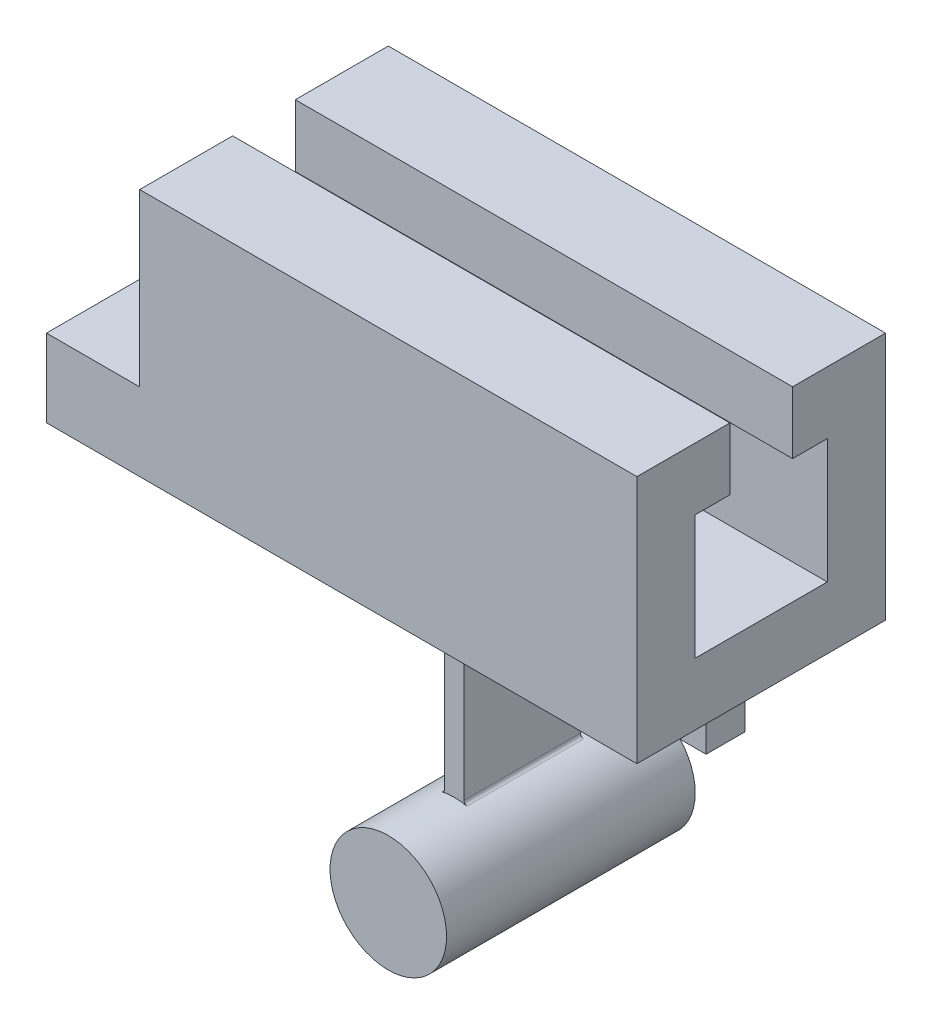
SolidWorks part; units mm, degrees
material "6061-T6 (SS)"
ref_plane "Front Plane" through (0, 0, 0) normal (0, 0, 1) x (1, 0, 0)
ref_plane "Top Plane" through (0, 0, 0) normal (0, 1, 0) x (1, 0, 0)
ref_plane "Right Plane" through (0, 0, 0) normal (1, 0, 0) x (0, 0, -1)
sketch "Sketch1" plane through (0, 0, 0) normal (1, 0, 0) x (0, 0, -1)
  line L1 (-25.4, -25.4) -> (25.4, -25.4)
  line L2 (-25.4, -25.4) -> (-25.4, 25.4)
  line L3 (-25.4, 25.4) -> (25.4, 25.4)
  line L4 (25.4, -25.4) -> (25.4, 25.4)
  line L5 (-25.4, -25.4) -> (25.4, 25.4) construction
  line L6 (-25.4, 25.4) -> (25.4, -25.4) construction
  point P0 (0, 0)
  dimension "D1" = 50.8
  dimension "D2" = 50.8
extrude "Boss-Extrude1" add sketch "Sketch1" along normal mid plane 101.6
sketch "Sketch2" plane through (50.8, 0, 0) normal (1, 0, 0) x (0, 0, -1)
  line L0 (0, 2.0782) -> (0, 27.4782) construction
  line L1 (25.4, 25.4) -> (-25.4, 25.4) construction
  line L2 (-6.4008, 25.4) -> (6.4008, 25.4)
  line L3 (-13.4938, 12.6848) -> (13.4937, 12.6848)
  line L4 (-13.4938, 12.6848) -> (-13.4938, -12.6848)
  line L5 (-13.4938, -12.6848) -> (13.4937, -12.6848)
  line L6 (13.4937, 12.6848) -> (13.4937, -12.6848)
  line L7 (-13.4938, 12.6848) -> (13.4937, -12.6848) construction
  line L8 (-13.4938, -12.6848) -> (13.4937, 12.6848) construction
  line L9 (-6.4008, 25.4) -> (-6.4008, 12.6848)
  line L10 (-6.4008, 12.6848) -> (6.4008, 12.6848)
  line L11 (6.4008, 25.4) -> (6.4008, 12.6848)
  line L12 (-6.4008, 25.4) -> (6.4008, 12.6848) construction
  line L13 (-6.4008, 12.6848) -> (6.4008, 25.4) construction
  point P1 (0, 0)
  point P2 (0, 19.0424)
  dimension "D1" = 38.0848
  dimension "D2" = 26.9875
  dimension "D3" = 12.8016
extrude "Cut-Extrude1" cut sketch "Sketch2" against normal through all contours L4 L3 L6 L5 | L9 L2 L11 L10
sketch "Sketch3" plane through (0, -25.4, 0) normal (0, -1, 0) x (1, 0, 0)
  line L1 (-1.9844, 11.9062) -> (1.9844, 11.9062)
  line L2 (-1.9844, 11.9062) -> (-1.9844, -11.9063)
  line L3 (-1.9844, -11.9063) -> (1.9844, -11.9063)
  line L4 (1.9844, 11.9062) -> (1.9844, -11.9063)
  line L5 (-1.9844, 11.9062) -> (1.9844, -11.9063) construction
  line L6 (-1.9844, -11.9063) -> (1.9844, 11.9062) construction
  point P0 (0, 0)
  dimension "D1" = 3.9688
  dimension "D2" = 23.8125
extrude "Boss-Extrude2" add sketch "Sketch3" along normal blind 50.0062
sketch "Sketch4" plane through (0, 0, 0) normal (0, 0, 1) x (1, 0, 0)
  line L0 (50.8, -25.4) -> (-50.8, -25.4) construction
  circle A0 centre (0, -75.4062) radius 11.9063
  dimension "D1" = 23.8125
  dimension "D2" = 50.0062
extrude "Boss-Extrude3" add sketch "Sketch4" along normal mid plane 50.8
sketch "Sketch5" plane through (-50.8, 0, 0) normal (-1, 0, 0) x (0, 0, 1)
  line L0 (25.4, 25.4) -> (25.4, -25.4) construction
  line L1 (-25.4, -25.4) -> (25.4, -25.4)
  line L2 (-25.4, -25.4) -> (-25.4, -9.525)
  line L3 (-25.4, -9.525) -> (25.4, -9.525)
  line L4 (25.4, -25.4) -> (25.4, -9.525)
  dimension "D1" = 15.875
extrude "Boss-Extrude4" add sketch "Sketch5" along normal blind 19.05
sketch "Sketch6" plane through (0, -25.4, 0) normal (0, -1, 0) x (1, 0, 0)
  line L1 (35.5613, 3.9687) -> (43.4988, 3.9687)
  line L2 (35.5613, 3.9687) -> (35.5613, -3.9688)
  line L3 (35.5613, -3.9688) -> (43.4988, -3.9688)
  line L4 (43.4988, 3.9687) -> (43.4988, -3.9688)
  line L5 (35.5613, 3.9687) -> (43.4988, -3.9688) construction
  line L6 (35.5613, -3.9688) -> (43.4988, 3.9687) construction
  point P0 (39.53, 0)
  dimension "D1" = 7.9375
  dimension "D2" = 7.9375
  dimension "D3" = 39.53
extrude "Boss-Extrude5" add sketch "Sketch6" along normal blind 12.7
fillet "Fillet1" radius 0.762 3 edges at (-50.8, -12.6848, 0) (1.9844, -63.6665, 0) (-1.9844, -63.6665, 0)
equation "\"F\"= 650"
equation "\"SF\"= 4"
equation "\"Sy\"= 35000"
equation "\"E\"= 10000000"
equation "\"sigma_allow\"= \"Sy\" / \"SF\""
equation "\"delta\"= 0.005"
equation "\"L_A\"= 1.0"
equation "\"L_B\"= 1.5"
equation "\"L_C\"= 4.0"
equation "\"L_D\"= 0.75"
equation "\"L_E\"= 0.5"
equation "\"a_pocket\"= 0.504"
equation "\"b_pocket\"=1.0625"
equation "\"c_pocket\"= 1.4994"
equation "\"floor\"= 0.5"
equation "\"d_A\"= 0.9375"
equation "\"w_B\"= \"d_A\""
equation "\"t_B\"=0.15625"
equation "\"h_C\"= 2"
equation "\"t_D\"= 0.625"
equation "\"s_E\"= 0.3125"
equation "\"D2@Sketch1\"=\"h_C\""
equation "\"D1@Boss-Extrude1\"=\"L_C\""
equation "\"D1@Sketch2\"=\"c_pocket\""
equation "\"D2@Sketch2\"=\"b_pocket\""
equation "\"D3@Sketch2\"=\"a_pocket\""
equation "\"D1@Sketch3\"=\"t_B\""
equation "\"D2@Sketch3\"=\"w_B\""
equation "\"D1@Sketch4\"=\"d_A\""
equation "\"D1@Sketch5\"=\"t_D\""
equation "\"D1@Boss-Extrude4\"=\"L_D\""
equation "\"D1@Sketch6\"=\"s_E\""
equation "\"D2@Sketch6\"=\"s_E\""
